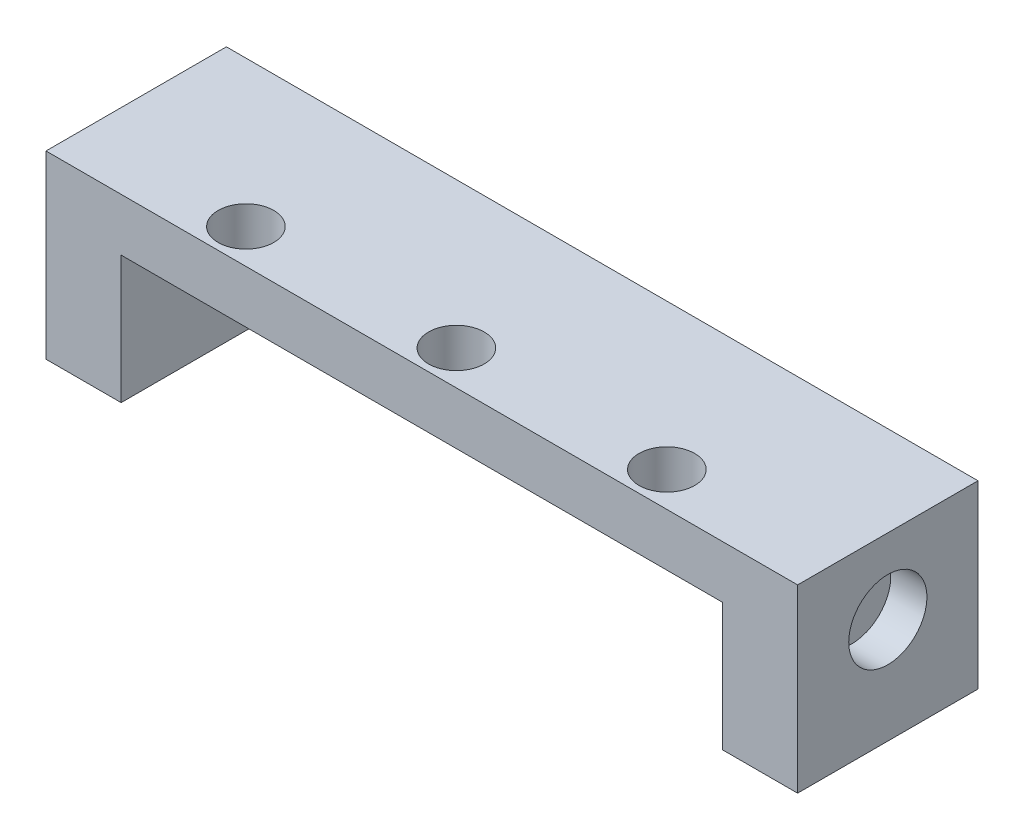
SolidWorks part; units mm, degrees
ref_plane "Front Plane" through (0, 0, 0) normal (0, 0, 1) x (1, 0, 0)
ref_plane "Top Plane" through (0, 0, 0) normal (0, 1, 0) x (1, 0, 0)
ref_plane "Right Plane" through (0, 0, 0) normal (1, 0, 0) x (0, 0, -1)
sketch "Sketch1" plane through (0, 0, 0) normal (0, 0, 1) x (1, 0, 0)
  line L1 (0, 0) -> (54, 0)
  line L2 (0, 0) -> (0, 59)
  line L3 (0, 59) -> (54, 59)
  line L4 (54, 0) -> (54, 59)
  line L8 (0, 59) -> (54, 0) construction
  line L10 (7, 3.5) -> (47, 3.5)
  line L11 (7, 3.5) -> (7, 55.5)
  line L12 (7, 55.5) -> (47, 55.5)
  line L13 (47, 3.5) -> (47, 55.5)
  line L14 (7, 3.5) -> (47, 55.5) construction
  line L15 (7, 55.5) -> (47, 3.5) construction
  point P5 (27, 29.5)
  dimension "D2" = 59
  dimension "D1" = 7
  dimension "D3" = 3.5
  dimension "D4" = 40
extrude "Boss-Extrude1" add sketch "Sketch1" along normal blind 12
sketch "Sketch2" plane through (0, 59, 0) normal (0, 1, 0) x (1, 0, 0)
  line L0 (13, -9.7) -> (41, -9.7) construction
  line L1 (27, 0) -> (27, -12) construction
  line L2 (54, 0) -> (0, 0) construction
  line L3 (54, -12) -> (0, -12) construction
  circle A0 centre (13, -9.7) radius 1.85
  circle A1 centre (41, -9.7) radius 1.85
  circle A2 centre (27, -9.7) radius 1.85
  point P11 (27, -6)
  dimension "D1" = 3.7
  dimension "D3" = 3.7
  dimension "D2" = 14
  dimension "D4" = 3.7
extrude "Cut-Extrude1" cut sketch "Sketch2" against normal blind 10
sketch "Sketch3" plane through (0, 0, 0) normal (0, -1, 0) x (1, 0, 0)
  line L0 (27, 0) -> (27, 12) construction
  line L1 (0, 0) -> (54, 0) construction
  line L2 (0, 12) -> (54, 12) construction
  line L3 (27, 6) -> (12.75, 6) construction
  circle A0 centre (12.75, 6) radius 1.85
  circle A1 centre (41.25, 6) radius 1.85
  dimension "D1" = 3.7
  dimension "D2" = 14.25
extrude "Cut-Extrude2" cut sketch "Sketch3" against normal blind 10
sketch "Sketch4" plane through (0, 0, 0) normal (0, -1, 0) x (1, 0, 0)
  line L4 (0, 0) -> (54, 0)
  line L5 (54, 0) -> (54, 12)
  line L6 (54, 12) -> (0, 12)
  line L7 (0, 12) -> (0, 0)
  line L8 (0, 0) -> (54, 0)
  line L9 (54, 0) -> (54, 12)
  line L10 (54, 12) -> (0, 12)
  line L11 (0, 12) -> (0, 0)
  dimension "D1" = 0
extrude "Cut-Extrude4" cut sketch "Sketch4" against normal blind 40
sketch "Sketch5" plane through (0, 40, 0) normal (0, -1, 0) x (1, 0, 0)
  line L4 (7, 12) -> (0, 12)
  line L5 (0, 12) -> (0, 0)
  line L6 (0, 0) -> (7, 0)
  line L7 (7, 0) -> (7, 12)
  line L8 (7, 12) -> (0, 12)
  line L9 (0, 12) -> (0, 0)
  line L10 (0, 0) -> (7, 0)
  line L11 (7, 0) -> (7, 12)
  line L12 (47, 0) -> (54, 0)
  line L13 (54, 0) -> (54, 12)
  line L14 (54, 12) -> (47, 12)
  line L15 (47, 12) -> (47, 0)
  line L16 (47, 0) -> (54, 0)
  line L17 (54, 0) -> (54, 12)
  line L18 (54, 12) -> (47, 12)
  line L19 (47, 12) -> (47, 0)
  dimension "D1" = 0
  dimension "D2" = 0
extrude "Cut-Extrude5" cut sketch "Sketch5" against normal blind 40
sketch "Sketch6" plane through (47, 0, 0) normal (1, 0, 0) x (0, 0, -1)
  line L1 (-12, 59) -> (0, 59)
  line L2 (-12, 59) -> (-12, 47)
  line L3 (-12, 47) -> (0, 47)
  line L4 (0, 59) -> (0, 47)
  dimension "D1" = 12
  dimension "D2" = 12
extrude "Boss-Extrude2" add sketch "Sketch6" along normal blind 5
ref_plane "Plane1" through (27, 0, 0) normal (-1, 0, 0) x (0, 0, 1)
mirror "Mirror1" about plane through (27, 0, 0) normal (-1, 0, 0) of "Boss-Extrude2"
sketch "Sketch7" plane through (2, 0, 0) normal (-1, 0, 0) x (0, 0, 1)
  line L0 (6, 59) -> (6, 47) construction
  line L1 (0, 59) -> (12, 59) construction
  line L2 (12, 47) -> (0, 47) construction
  circle A0 centre (6, 54) radius 2.6
  dimension "D1" = 5
  dimension "D2" = 5.2
extrude "Cut-Extrude6" cut sketch "Sketch7" against normal blind 2.4
mirror "Mirror2" about plane through (27, 0, 0) normal (-1, 0, 0) of "Cut-Extrude6"
